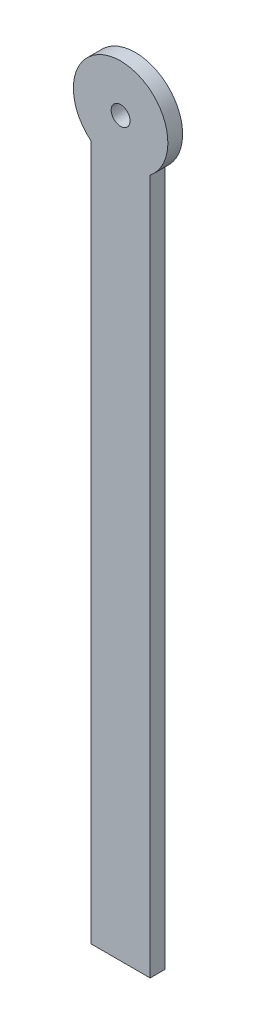
SolidWorks part; units mm, degrees
ref_plane "Front Plane" through (0, 0, 0) normal (0, 0, 1) x (1, 0, 0)
ref_plane "Top Plane" through (0, 0, 0) normal (0, 1, 0) x (1, 0, 0)
ref_plane "Right Plane" through (0, 0, 0) normal (1, 0, 0) x (0, 0, -1)
sketch "Sketch1" plane through (0, 0, 0) normal (0, 0, 1) x (1, 0, 0)
  line L0 (0, 179.6468) -> (0, -115.9426) construction
  line L1 (6.35, 0) -> (-6.35, 0)
  line L2 (-6.35, 0) -> (-6.35, 165.1)
  line L3 (-6.35, 165.1) -> (6.35, 165.1)
  line L4 (6.35, 0) -> (6.35, 165.1)
  point P7 (0, 0)
  point P9 (0, 165.1)
  dimension "D1" = 6.35
  dimension "D2" = 165.1
extrude "Boss-Extrude1" add sketch "Sketch1" along normal blind 3.175
sketch "Sketch3" plane through (0, 0, 3.175) normal (0, 0, 1) x (1, 0, 0)
  line L2 (6.35, 165.1) -> (-6.35, 165.1) construction
  line L3 (-6.35, 165.1) -> (-6.35, 0) construction
  circle A0 centre (0, 157.48) radius 10.16
  dimension "D1" = 20.32
  dimension "D2" = 7.62
  dimension "D3" = 6.35
extrude "Boss-Extrude2" add sketch "Sketch3" against normal up to surface (3.175 mm away) up to face at (0, 82.55, 0)
sketch "Sketch4" plane through (0, 0, 3.175) normal (0, 0, 1) x (1, 0, 0)
  circle A0 centre (0, 157.48) radius 2.032
  dimension "D1" = 4.064
extrude "Cut-Extrude2" cut sketch "Sketch4" against normal through all
